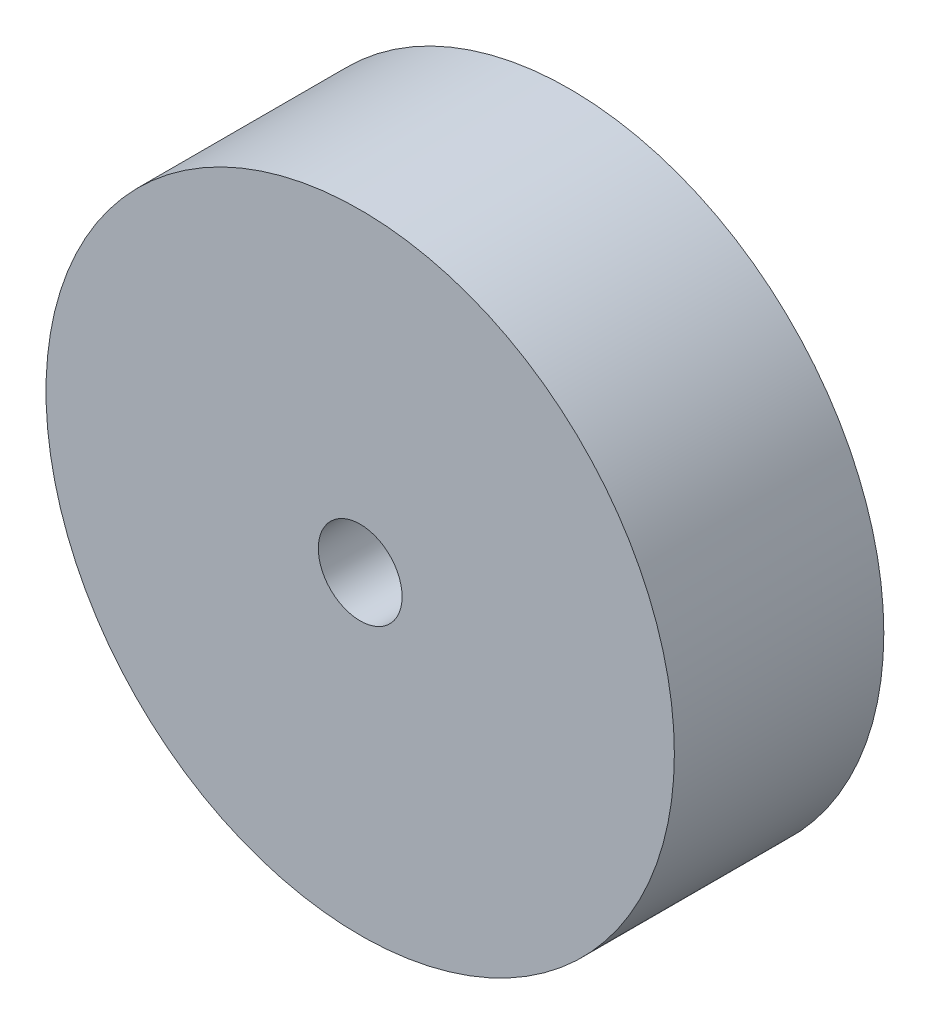
SolidWorks part; units mm, degrees
ref_plane "前视基准面" through (0, 0, 0) normal (0, 0, 1) x (1, 0, 0)
ref_plane "上视基准面" through (0, 0, 0) normal (0, 1, 0) x (1, 0, 0)
ref_plane "右视基准面" through (0, 0, 0) normal (1, 0, 0) x (0, 0, -1)
sketch "草图1" plane through (0, 0, 0) normal (0, 0, 1) x (1, 0, 0)
  circle A0 centre (0, 0) radius 15
  circle A1 centre (0, 0) radius 2
  dimension "D1" = 30
extrude "凸台-拉伸1" add sketch "草图1" along normal blind 10
